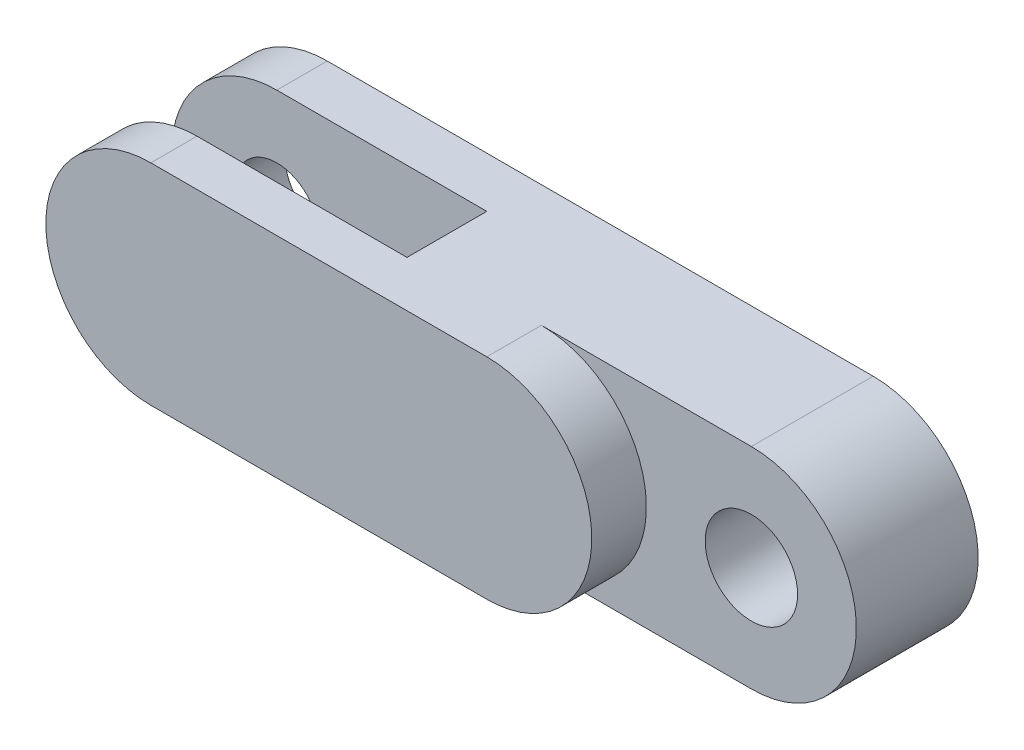
SolidWorks part; units mm, degrees
ref_plane "Front Plane" through (0, 0, 0) normal (0, 0, 1) x (1, 0, 0)
ref_plane "Top Plane" through (0, 0, 0) normal (0, 1, 0) x (1, 0, 0)
ref_plane "Right Plane" through (0, 0, 0) normal (1, 0, 0) x (0, 0, -1)
sketch "Sketch1" plane through (0, 0, 0) normal (0, 0, 1) x (1, 0, 0)
  line L0 (6.5, 0) -> (-6.5, 0) construction
  line L1 (6.5, -2.5) -> (-6.5, -2.5)
  line L2 (6.5, 2.5) -> (-6.5, 2.5)
  arc A0 (6.5, -2.5) -> (6.5, 2.5) centre (6.5, 0) ccw
  arc A1 (-6.5, 2.5) -> (-6.5, -2.5) centre (-6.5, 0) ccw
  point P2 (0, 0)
  dimension "D2" = 2.5
  dimension "D1" = 13
extrude "Boss-Extrude1" add sketch "Sketch1" along normal mid plane 4.2
sketch "Sketch2" plane through (0, 0, 2.1) normal (0, 0, 1) x (1, 0, 0)
  line L0 (-6.5, 0) -> (1.5, 0) construction
  line L1 (-6.5, 2.5) -> (1.5, 2.5)
  line L2 (-6.5, -2.5) -> (1.5, -2.5)
  line L4 (6.5, 2.5) -> (-6.5, 2.5) construction
  arc A0 (-6.5, 2.5) -> (-6.5, -2.5) centre (-6.5, 0) ccw
  arc A1 (1.5, -2.5) -> (1.5, 2.5) centre (1.5, 0) ccw
  arc A4 (-6.5, 2.5) -> (-6.5, -2.5) centre (-6.5, 0) ccw construction
  point P3 (-2.5, 0)
  arc M6 (6.5, -2.5) -> (6.5, 2.5) centre (6.5, 0) ccw
  line M7 (6.5, 2.5) -> (-6.5, 2.5)
  line M9 (-6.5, -2.5) -> (6.5, -2.5)
  dimension "D1" = 8
extrude "Cut-Extrude1" cut sketch "Sketch2" against normal blind 1.3 contours A1 M9 M6 M7
sketch "Sketch3" plane through (0, 0, 0.8) normal (0, 0, 1) x (1, 0, 0)
  circle A0 centre (6.5, 0) radius 1.1
  dimension "D1" = 2.2
extrude "Cut-Extrude2" cut sketch "Sketch3" against normal through all
sketch "Sketch4" plane through (0, 0, 0) normal (0, 1, 0) x (1, 0, 0)
  line L8 (-9, 2.1) -> (-9, -2.1) construction
  line L18 (-9, 0.9) -> (-1.5, 0.9)
  line L19 (-9, 0.9) -> (-9, -1)
  line L20 (-9, -1) -> (-1.5, -1)
  line L21 (-1.5, 0.9) -> (-1.5, -1)
  line L22 (-6.5, 2.1) -> (-9, 2.1) construction
  dimension "D1" = 1.2
  dimension "D2" = 3.1
  dimension "D3" = 7.5
extrude "Cut-Extrude3" cut sketch "Sketch4" against normal through all both and the other way through all contours L18 L21 L20 L19
sketch "Sketch5" plane through (0, 0, -0.9) normal (0, 0, 1) x (1, 0, 0)
  circle A0 centre (-6.5, 0) radius 1
  dimension "D1" = 2
extrude "Cut-Extrude4" cut sketch "Sketch5" against normal through all
